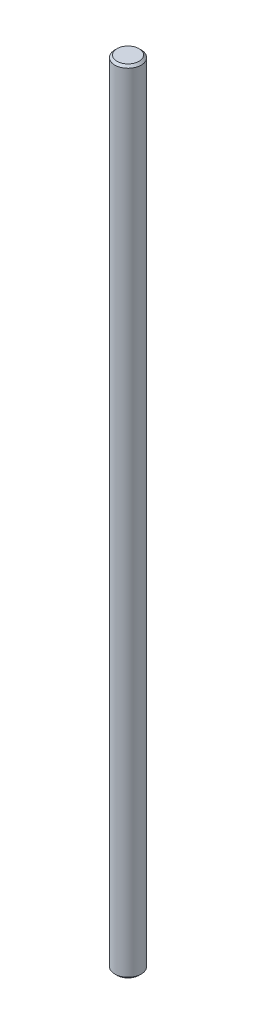
SolidWorks part; units mm, degrees
material "Gri Dökme Demir"
ref_plane "Ön Düzlem" through (0, 0, 0) normal (0, 0, 1) x (1, 0, 0)
ref_plane "Üst Düzlem" through (0, 0, 0) normal (0, 1, 0) x (1, 0, 0)
ref_plane "Sağ Düzlem" through (0, 0, 0) normal (1, 0, 0) x (0, 0, -1)
sketch "Çizim1" plane through (0, 0, 0) normal (0, 1, 0) x (1, 0, 0)
  circle A0 centre (0, 0) radius 3
  dimension "D1" = 6
extrude "Yükseklik-Ekstrüzyon1" add sketch "Çizim1" along normal blind 180
chamfer "Pah1" distance 0.5 angle 45 2 edges at (0, 0, 3) (0, 180, 3)
